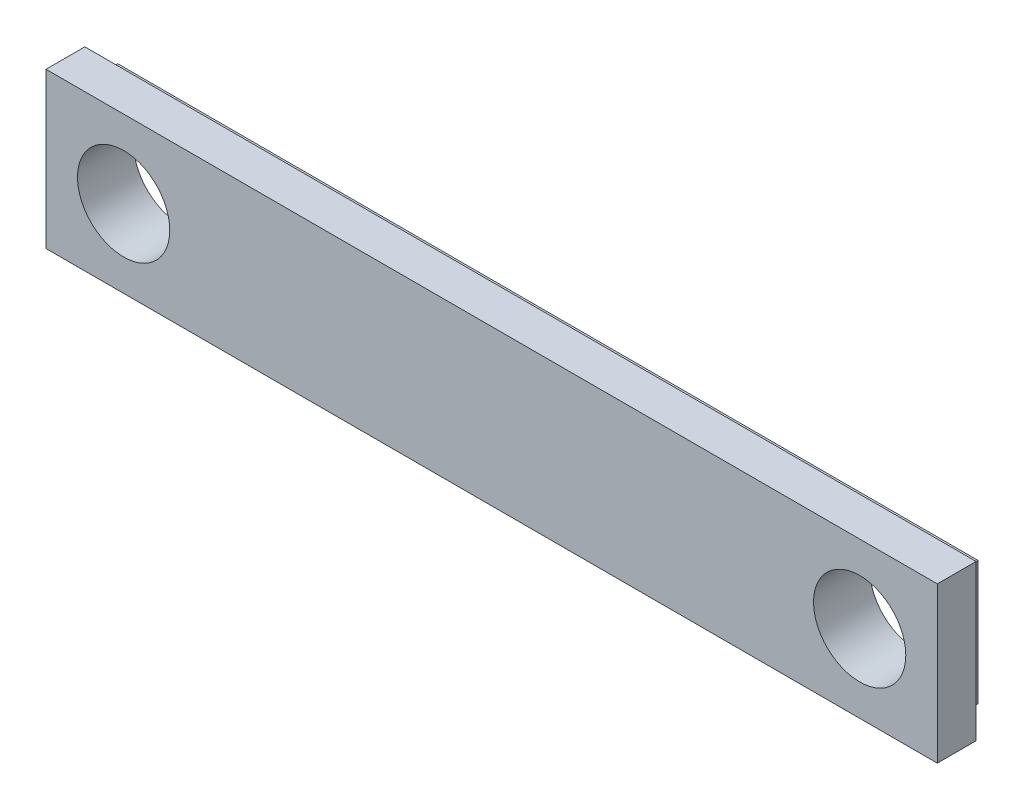
SolidWorks part; units mm, degrees
ref_plane "Front Plane" through (0, 0, 0) normal (0, 0, 1) x (1, 0, 0)
ref_plane "Top Plane" through (0, 0, 0) normal (0, 1, 0) x (1, 0, 0)
ref_plane "Right Plane" through (0, 0, 0) normal (1, 0, 0) x (0, 0, -1)
sketch "Sketch1" plane through (0, 0, 0.932) normal (0, 0, 1) x (1, 0, 0)
  line L0 (161.9, 2) -> (161.9, 10)
  line L1 (161.4, 1.5) -> (217.8, 1.5) construction
  line L2 (161.4, 1.5) -> (161.4, 10.5) construction
  line L3 (161.4, 10.5) -> (217.8, 10.5) construction
  line L4 (217.8, 1.5) -> (217.8, 10.5) construction
  line L5 (161.9, 10) -> (217.3, 10)
  line L6 (217.3, 2) -> (217.3, 10)
  line L7 (161.9, 2) -> (217.3, 2)
  line L8 (217.8, 1.5) -> (217.8, 10.5) construction
  line L9 (189.6, 1.5) -> (217.8, 1.5) construction
  line L10 (217.8, 10.5) -> (189.6, 10.5) construction
  line L11 (161.4, 1.5) -> (161.4, 10.5) construction
  circle A0 centre (165.9, 6) radius 2.97
  circle A1 centre (213.3, 6) radius 2.97
  point P24 (217.3, 6)
  point P25 (161.9, 6)
  dimension "D2" = 5.94
  dimension "D3" = 4.5
  dimension "D4" = 4.5
  dimension "D1" = 0.5
extrude "Boss-Extrude1" add sketch "Sketch1" along normal blind 1.12
sketch "Sketch2" plane through (0, 0, 2.052) normal (0, 0, 1) x (1, 0, 0)
  line L0 (217.3, 10) -> (161.9, 10) construction
  line L1 (161.9, 2) -> (217.3, 2) construction
  line L2 (161.9, 2) -> (161.9, 10) construction
  line L3 (161.9, 10) -> (217.3, 10) construction
  line L4 (217.3, 2) -> (217.3, 10) construction
  line L5 (161.9, 10) -> (161.9, 2) construction
  line L7 (160.9, 11) -> (218.3, 11)
  line L8 (218.3, 1) -> (218.3, 11)
  line L9 (160.9, 1) -> (218.3, 1)
  line L10 (160.9, 1) -> (160.9, 11)
  circle A0 centre (213.3, 6) radius 2.97
  circle A1 centre (165.9, 6) radius 2.97
  circle A2 centre (165.9, 6) radius 2.97 construction
  circle A3 centre (213.3, 6) radius 2.97 construction
  point P4 (189.6, 10)
  point P7 (189.6, 10)
  point P8 (161.9, 6)
  point P11 (161.9, 6)
  point P24 (212.8, 6)
  point P25 (212.8, 6)
  dimension "D1" = 1
extrude "Boss-Extrude2" add sketch "Sketch2" along normal blind 2.5
